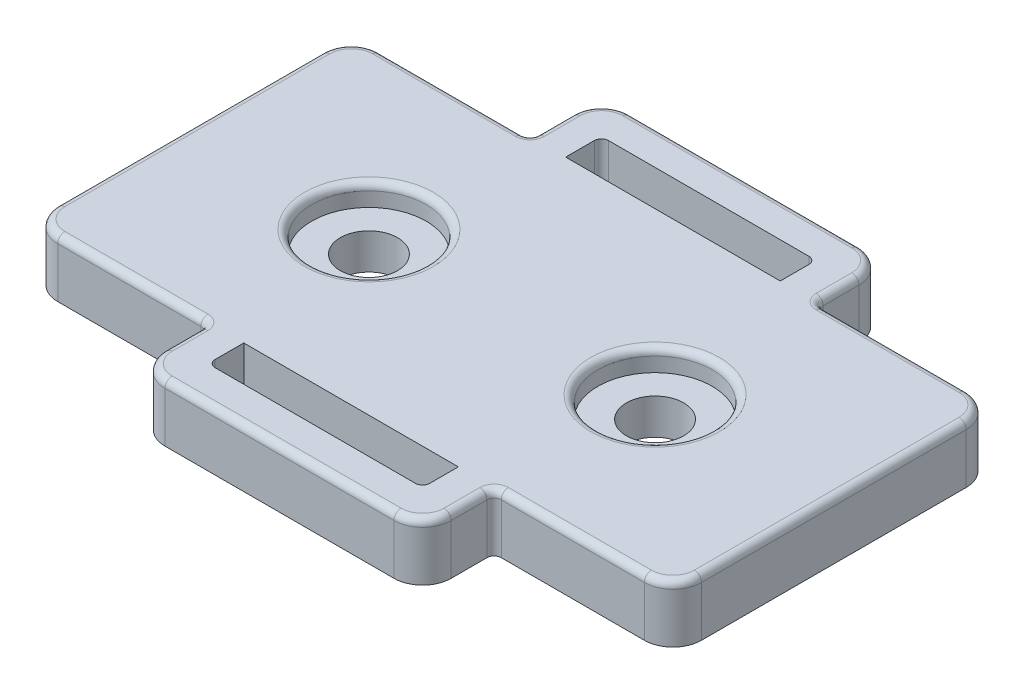
SolidWorks part; units mm, degrees
ref_plane "前视基准面" through (0, 0, 0) normal (0, 0, 1) x (1, 0, 0)
ref_plane "上视基准面" through (0, 0, 0) normal (0, 1, 0) x (1, 0, 0)
ref_plane "右视基准面" through (0, 0, 0) normal (1, 0, 0) x (0, 0, -1)
other "Configuration Table"
sketch "草图1" plane through (0, 0, 0) normal (0, 1, 0) x (1, 0, 0)
  line L0 (-20, 0) -> (20, 0) construction
  line L1 (-41, -22.5) -> (-21, -22.5)
  line L2 (-45, -18.5) -> (-45, 18.5)
  line L3 (-41, 22.5) -> (-21, 22.5)
  line L4 (45, -18.5) -> (45, 18.5)
  line L5 (-45, -22.5) -> (45, 22.5) construction
  line L6 (-45, 22.5) -> (45, -22.5) construction
  line L7 (-20, 23.5) -> (-20, 28.5)
  line L8 (-16, 32.5) -> (16, 32.5)
  line L9 (20, 28.5) -> (20, 23.5)
  line L10 (-20, 22.5) -> (-15, 22.5) construction
  line L11 (-15, 22.5) -> (-15, 26.5)
  line L12 (-14, 27.5) -> (14, 27.5)
  line L13 (15, 26.5) -> (15, 22.5)
  line L14 (15, -26.5) -> (15, -22.5)
  line L15 (-14, -27.5) -> (14, -27.5)
  line L16 (-15, -22.5) -> (-15, -26.5)
  line L17 (20, -28.5) -> (20, -23.5)
  line L18 (-16, -32.5) -> (16, -32.5)
  line L19 (-20, -23.5) -> (-20, -28.5)
  line L20 (-15, -22.5) -> (15, -22.5)
  line L21 (-20, -22.5) -> (-15, -22.5) construction
  line L22 (21, -22.5) -> (41, -22.5)
  line L23 (15, -22.5) -> (20, -22.5) construction
  line L24 (-15, 22.5) -> (15, 22.5)
  line L25 (-20, 22.5) -> (-15, 22.5) construction
  line L26 (21, 22.5) -> (41, 22.5)
  line L27 (15, 22.5) -> (20, 22.5) construction
  arc A0 (-41, -22.5) -> (-45, -18.5) centre (-41, -18.5) cw
  arc A1 (41, -22.5) -> (45, -18.5) centre (41, -18.5) ccw
  arc A2 (41, 22.5) -> (45, 18.5) centre (41, 18.5) cw
  arc A3 (-45, 18.5) -> (-41, 22.5) centre (-41, 18.5) cw
  circle A4 centre (-20, 0) radius 4
  circle A5 centre (20, 0) radius 4
  arc A6 (14, 27.5) -> (15, 26.5) centre (14, 26.5) cw
  arc A7 (-15, 26.5) -> (-14, 27.5) centre (-14, 26.5) cw
  arc A8 (16, 32.5) -> (20, 28.5) centre (16, 28.5) cw
  arc A9 (-20, 28.5) -> (-16, 32.5) centre (-16, 28.5) cw
  arc A10 (-20, -28.5) -> (-16, -32.5) centre (-16, -28.5) ccw
  arc A11 (16, -32.5) -> (20, -28.5) centre (16, -28.5) ccw
  arc A12 (-15, -26.5) -> (-14, -27.5) centre (-14, -26.5) ccw
  arc A13 (14, -27.5) -> (15, -26.5) centre (14, -26.5) ccw
  arc A14 (20, -23.5) -> (21, -22.5) centre (21, -23.5) cw
  arc A15 (-20, -23.5) -> (-21, -22.5) centre (-21, -23.5) ccw
  arc A16 (20, 23.5) -> (21, 22.5) centre (21, 23.5) ccw
  arc A17 (-20, 23.5) -> (-21, 22.5) centre (-21, 23.5) cw
  point P0 (0, 0)
  point P21 (0, 0)
  point P33 (15, 27.5)
  point P36 (-15, 27.5)
  point P39 (20, 32.5)
  point P42 (-20, 32.5)
  point P59 (-20, -32.5)
  point P60 (20, -32.5)
  point P61 (-15, -27.5)
  point P62 (15, -27.5)
  point P63 (0, 0)
  dimension "D3" = 4
  dimension "D5" = 8
  dimension "D6" = 8
  dimension "D13" = 1
  dimension "D14" = 4
  dimension "D15" = 1
  dimension "D1" = 45
  dimension "D2" = 90
  dimension "D4" = 40
  dimension "D7" = 10
  dimension "D8" = 5
  dimension "D9" = 30
  dimension "D10" = 40
  dimension "D11" = 5
  dimension "D12" = 5
extrude "凸台-拉伸1" add sketch "草图1" along normal blind 8
sketch "草图2" plane through (0, 8, 0) normal (0, 1, 0) x (1, 0, 0)
  circle A0 centre (-20, 0) radius 8
  circle A1 centre (20, 0) radius 8
  dimension "D1" = 16
  dimension "D2" = 16
extrude "切除-拉伸1" cut sketch "草图2" against normal blind 3
sketch "草图3" plane through (0, 0, 0) normal (0, -1, 0) x (1, 0, 0)
  line L1 (-8.5, -15) -> (8.5, -15)
  line L2 (-12.5, -11) -> (-12.5, 11)
  line L3 (-8.5, 15) -> (8.5, 15)
  line L4 (12.5, -11) -> (12.5, 11)
  line L5 (-12.5, -15) -> (12.5, 15) construction
  line L6 (-12.5, 15) -> (12.5, -15) construction
  arc A0 (8.5, -15) -> (12.5, -11) centre (8.5, -11) ccw
  arc A1 (-8.5, -15) -> (-12.5, -11) centre (-8.5, -11) cw
  arc A2 (8.5, 15) -> (12.5, 11) centre (8.5, 11) cw
  arc A3 (-12.5, 11) -> (-8.5, 15) centre (-8.5, 11) cw
  point P0 (0, 0)
  dimension "D3" = 4
  dimension "D1" = 30
  dimension "D2" = 25
extrude "切除-拉伸2" cut sketch "草图3" against normal blind 3
fillet "圆角1" radius 1 26 edges at (-43.8284, 8, 21.3284) (-45, 8, 0) (-43.8284, 8, -21.3284) (-31, 8, -22.5) (43.8284, 8, -21.3284) (45, 8, 0) (43.8284, 8, 21.3284) (20, 8, 8) (-20, 8, 8) (-31, 8, 22.5) (-20.2929, 8, -22.7929) (-20, 8, -26) (-18.8284, 8, -31.3284) (0, 8, -32.5) (18.8284, 8, -31.3284) (20, 8, -26) (20.2929, 8, -22.7929) (31, 8, -22.5) (31, 8, 22.5) (20.2929, 8, 22.7929) (20, 8, 26) (18.8284, 8, 31.3284) (0, 8, 32.5) (-18.8284, 8, 31.3284) (-20, 8, 26) (-20.2929, 8, 22.7929)
